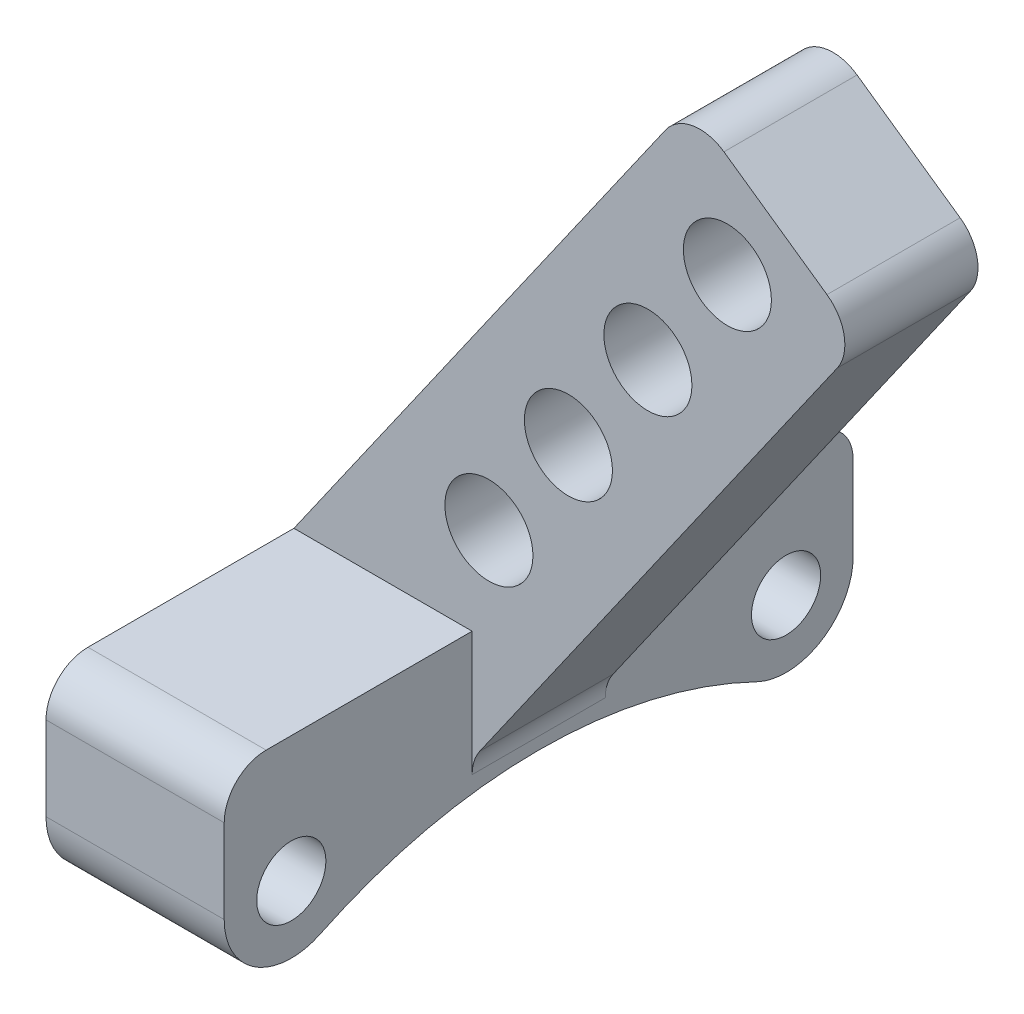
SolidWorks part; units mm, degrees
material "ABS"
ref_plane "Front Plane" through (0, 0, 0) normal (0, 0, 1) x (1, 0, 0)
ref_plane "Top Plane" through (0, 0, 0) normal (0, 1, 0) x (1, 0, 0)
ref_plane "Right Plane" through (0, 0, 0) normal (1, 0, 0) x (0, 0, -1)
sketch "Sketch1" plane through (0, 0, 0) normal (1, 0, 0) x (0, 0, -1)
  line L0 (-11.8, 0) -> (-15, 0) construction
  line L1 (-13, -6) -> (13, -6)
  line L2 (-15, -4) -> (-15, 4)
  line L3 (-13, 6) -> (13, 6)
  line L4 (15, -4) -> (15, 4)
  line L5 (-15, -6) -> (15, 6) construction
  line L6 (-15, 6) -> (15, -6) construction
  line L7 (11.8, 0) -> (15, 0)
  circle A0 centre (-11.8, 0) radius 1.65
  circle A1 centre (11.8, 0) radius 1.65
  arc A2 (15, 4) -> (13, 6) centre (13, 4) ccw
  arc A3 (13, -6) -> (15, -4) centre (13, -4) ccw
  arc A4 (-13, -6) -> (-15, -4) centre (-13, -4) cw
  arc A5 (-15, 4) -> (-13, 6) centre (-13, 4) cw
  point P0 (0, 0)
  dimension "D3" = 3.3
  dimension "D5" = 2
  dimension "D1" = 30
  dimension "D2" = 12
  dimension "D4" = 23.6
extrude "Boss-Extrude1" add sketch "Sketch1" along normal blind 8.5
sketch "Sketch2" plane through (0, 0, 0) normal (0, 0, 1) x (1, 0, 0)
  line L0 (25.9181, 25.5805) -> (3.8053, -6)
  line L1 (25.427, 28.3659) -> (20.5121, 31.8074)
  line L2 (3.8053, -6) -> (-4.3863, -0.2642) construction
  line L3 (17.7266, 31.3162) -> (-4.3863, -0.2642) construction
  line L4 (22.9695, 30.0866) -> (-0.2905, -3.1321) construction
  line L5 (8.5, -4) -> (0, -4) construction
  line L6 (3.8053, -6) -> (0, -3.3355)
  line L7 (8.5, -6) -> (0, -6) construction
  line L8 (20.6752, 26.81) -> (16.8839, 21.3954) construction
  line L9 (16.8839, 21.3954) -> (13.0925, 15.9808) construction
  line L10 (13.0925, 15.9808) -> (9.3012, 10.5663) construction
  line L11 (0, -4) -> (0, 4) construction
  line L12 (10.9879, 4.2579) -> (2.7964, 9.9937) construction
  line L13 (0, -3.3355) -> (0, 6)
  line L14 (0, 6) -> (17.7266, 31.3162)
  circle A0 centre (20.6752, 26.81) radius 2.1
  circle A1 centre (16.8839, 21.3954) radius 2.1
  circle A2 centre (13.0925, 15.9808) radius 2.1
  circle A3 centre (9.3012, 10.5663) radius 2.1
  arc A4 (17.7266, 31.3162) -> (20.5121, 31.8074) centre (19.3649, 30.1691) cw
  arc A5 (25.9181, 25.5805) -> (25.427, 28.3659) centre (24.2798, 26.7276) ccw
  point P22 (18.8738, 32.9545)
  point P29 (27.0653, 27.2188)
  dimension "D4" = 4.2
  dimension "D6" = 6.61
  dimension "D9" = 2
  dimension "D1" = 55
  dimension "D2" = 10
  dimension "D3" = 4.2
  dimension "D5" = 4
  dimension "D7" = 6.61
  dimension "D8" = 6.61
extrude "Boss-Extrude2" add sketch "Sketch2" along normal mid plane 6.35
fillet "Fillet1" radius 2 1 edges at (8.5, 0.7048, 0)
sketch "Sketch4" plane through (8.5, 0, 0) normal (1, 0, 0) x (0, 0, -1)
  line L0 (-13, -6) -> (13, -6) construction
  line L1 (0, -0.5) -> (0, -6) construction
  line L2 (-15, -4) -> (-15, 4) construction
  line L3 (15, -4) -> (15, 4) construction
  line L4 (-15, 0) -> (-15, -4)
  line L5 (-13, -6) -> (13, -6)
  line L6 (15, -4) -> (15, 0)
  line L7 (-11.8, -3.2) -> (-11.8, -1.65) construction
  line L8 (-15, 0) -> (15, 0) construction
  arc A0 (-10.4084, -2.8816) -> (10.4084, -2.8816) centre (0, -24.4352) cw
  arc A1 (-10.4084, -2.8816) -> (-15, 0) centre (-11.8, 0) cw
  arc A2 (15, 0) -> (10.4084, -2.8816) centre (11.8, 0) cw
  circle A3 centre (-11.8, 0) radius 1.65 construction
  arc A4 (-13, -6) -> (-15, -4) centre (-13, -4) cw
  arc A5 (13, -6) -> (15, -4) centre (13, -4) ccw
  point P29 (0, -6)
  dimension "D1" = 5.5
extrude "Cut-Extrude1" cut sketch "Sketch4" against normal blind 10
